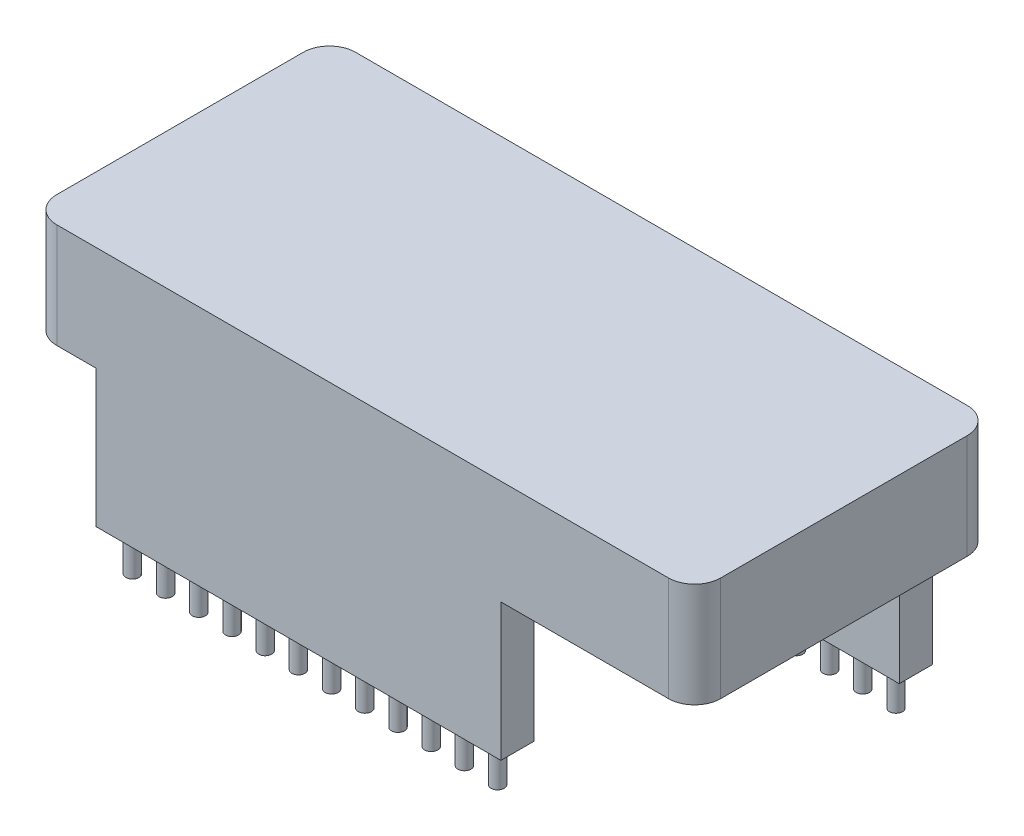
SolidWorks part; units mm, degrees
ref_plane "Front Plane" through (0, 0, 0) normal (0, 0, 1) x (1, 0, 0)
ref_plane "Top Plane" through (0, 0, 0) normal (0, 1, 0) x (1, 0, 0)
ref_plane "Right Plane" through (0, 0, 0) normal (1, 0, 0) x (0, 0, -1)
sketch "Sketch1" plane through (0, 0, 0) normal (0, 1, 0) x (1, 0, 0)
  line L1 (2, 0) -> (48.8, 0)
  line L2 (0, 2) -> (0, 20.86)
  line L3 (2, 22.86) -> (48.8, 22.86)
  line L4 (50.8, 2) -> (50.8, 20.86)
  arc A0 (48.8, 22.86) -> (50.8, 20.86) centre (48.8, 20.86) cw
  arc A1 (48.8, 0) -> (50.8, 2) centre (48.8, 2) ccw
  arc A2 (2, 0) -> (0, 2) centre (2, 2) cw
  arc A3 (0, 20.86) -> (2, 22.86) centre (2, 20.86) cw
  point P7 (50.8, 22.86)
  point P10 (50.8, 0)
  point P13 (0, 0)
  point P16 (0, 22.86)
  dimension "D3" = 2
  dimension "D1" = 22.86
  dimension "D2" = 50.8
extrude "Boss-Extrude1" add sketch "Sketch1" along normal blind 8
sketch "Sketch2" plane through (0, 0, 0) normal (0, -1, 0) x (1, 0, 0)
  line L0 (2, 0) -> (48.8, 0) construction
  line L1 (5, 0) -> (35.98, 0)
  line L2 (5, 0) -> (5, -2.54)
  line L3 (5, -2.54) -> (35.98, -2.54)
  line L4 (35.98, 0) -> (35.98, -2.54)
  line L5 (48.8, -22.86) -> (2, -22.86) construction
  line L6 (5, -22.86) -> (46.14, -22.86)
  line L7 (5, -22.86) -> (5, -20.32)
  line L8 (5, -20.32) -> (46.14, -20.32)
  line L9 (46.14, -22.86) -> (46.14, -20.32)
  line L10 (0, -20.86) -> (0, -2) construction
  point P12 (26.4414, -2.54)
  point P13 (8.5809, -2.54)
  dimension "D1" = 2.54
  dimension "D2" = 30.98
  dimension "D3" = 41.14
  dimension "D4" = 5
extrude "Boss-Extrude2" add sketch "Sketch2" along normal blind 10.5
sketch "Sketch3" plane through (0, -10.5, 0) normal (0, -1, 0) x (1, 0, 0)
  line L0 (6.52, 0) -> (6.52, -2.54) construction
  line L1 (35.98, 0) -> (5, 0) construction
  line L2 (5, -2.54) -> (35.98, -2.54) construction
  line L3 (5, 0) -> (5, -2.54) construction
  line L4 (6.52, -20.32) -> (6.52, -22.86) construction
  line L5 (46.14, -20.32) -> (5, -20.32) construction
  line L6 (5, -22.86) -> (46.14, -22.86) construction
  circle A0 centre (6.52, -1.27) radius 0.5
  circle A1 centre (9.06, -1.27) radius 0.5
  circle A2 centre (11.6, -1.27) radius 0.5
  circle A3 centre (14.14, -1.27) radius 0.5
  circle A4 centre (16.68, -1.27) radius 0.5
  circle A5 centre (19.22, -1.27) radius 0.5
  circle A6 centre (21.76, -1.27) radius 0.5
  circle A7 centre (24.3, -1.27) radius 0.5
  circle A8 centre (26.84, -1.27) radius 0.5
  circle A9 centre (29.38, -1.27) radius 0.5
  circle A10 centre (31.92, -1.27) radius 0.5
  circle A11 centre (34.46, -1.27) radius 0.5
  circle A12 centre (6.52, -21.59) radius 0.5
  circle A13 centre (9.06, -21.59) radius 0.5
  circle A14 centre (11.6, -21.59) radius 0.5
  circle A15 centre (14.14, -21.59) radius 0.5
  circle A16 centre (16.68, -21.59) radius 0.5
  circle A17 centre (19.22, -21.59) radius 0.5
  circle A18 centre (21.76, -21.59) radius 0.5
  circle A19 centre (24.3, -21.59) radius 0.5
  circle A20 centre (26.84, -21.59) radius 0.5
  circle A21 centre (29.38, -21.59) radius 0.5
  circle A22 centre (31.92, -21.59) radius 0.5
  circle A23 centre (34.46, -21.59) radius 0.5
  circle A24 centre (37, -21.59) radius 0.5
  circle A25 centre (39.54, -21.59) radius 0.5
  circle A26 centre (42.08, -21.59) radius 0.5
  circle A27 centre (44.62, -21.59) radius 0.5
  point P9 (6.52, -1.27)
  point P42 (6.52, -21.59)
  dimension "D1" = 1
  dimension "D2" = 1.52
  dimension "D3" = 12
  dimension "D4" = 16
extrude "Boss-Extrude3" add sketch "Sketch3" along normal blind 3
